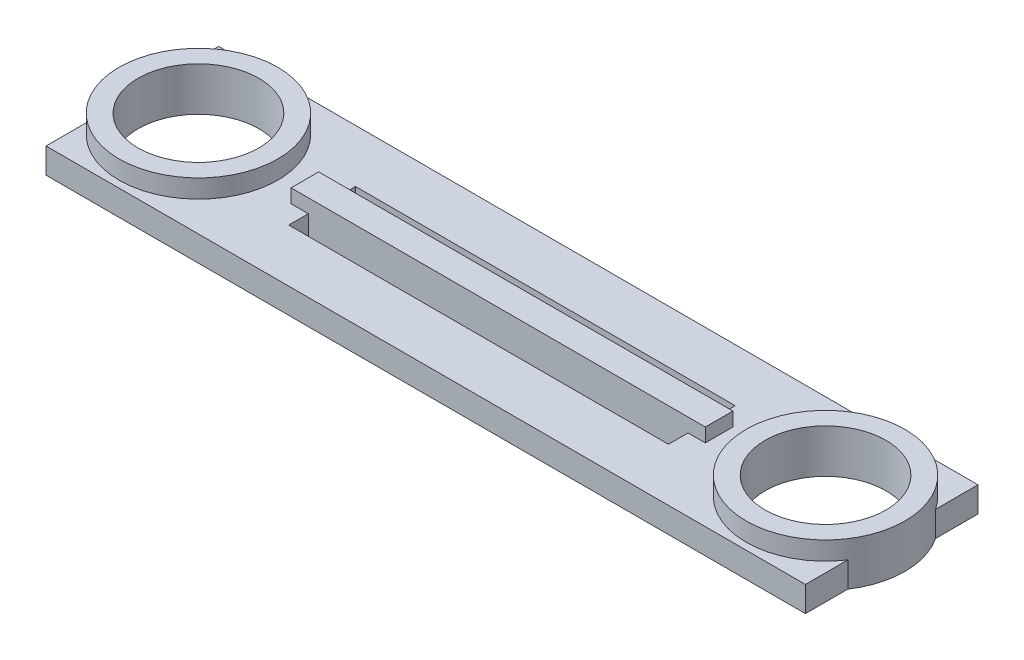
SolidWorks part; units mm, degrees
ref_plane "前视基准面" through (0, 0, 0) normal (0, 0, 1) x (1, 0, 0)
ref_plane "上视基准面" through (0, 0, 0) normal (0, 1, 0) x (1, 0, 0)
ref_plane "右视基准面" through (0, 0, 0) normal (1, 0, 0) x (0, 0, -1)
other "Configuration Table"
sketch "01_Link_Profile" plane through (0, 0, 0) normal (0, 1, 0) x (1, 0, 0)
  line L1 (-330, -75) -> (330, -75)
  line L2 (-330, -75) -> (-330, 75)
  line L3 (-330, 75) -> (330, 75)
  line L4 (330, -75) -> (330, 75)
  line L5 (-330, -75) -> (330, 75) construction
  line L6 (-330, 75) -> (330, -75) construction
  line L7 (-165, -29) -> (165, -29)
  line L8 (-165, -29) -> (-165, 29)
  line L9 (-165, 29) -> (165, 29)
  line L10 (165, -29) -> (165, 29)
  line L11 (-165, -29) -> (165, 29) construction
  line L12 (-165, 29) -> (165, -29) construction
  circle A0 centre (-272.5, 0) radius 52.5
  circle A1 centre (272.5, 0) radius 52.5
  point P0 (0, 0)
  point P10 (0, 0)
extrude "01_Link_Plate" add sketch "01_Link_Profile" along normal blind 22
sketch "02_End_Boss_Profiles" plane through (0, 0, 0) normal (0, 1, 0) x (1, 0, 0)
  circle A0 centre (-272.5, 0) radius 69
  circle A1 centre (-272.5, 0) radius 52.5
  circle A2 centre (272.5, 0) radius 69
  circle A3 centre (272.5, 0) radius 52.5
extrude "02_Bearing_Seat_Bosses" add sketch "02_End_Boss_Profiles" along normal blind 38
sketch "03_Center_Rib_Profile" plane through (0, 0, 0) normal (0, 1, 0) x (1, 0, 0)
  line L1 (-180, -12) -> (180, -12)
  line L2 (-180, -12) -> (-180, 12)
  line L3 (-180, 12) -> (180, 12)
  line L4 (180, -12) -> (180, 12)
  line L5 (-180, -12) -> (180, 12) construction
  line L6 (-180, 12) -> (180, -12) construction
  point P0 (0, 0)
extrude "03_Center_Rib" add sketch "03_Center_Rib_Profile" along normal blind 34
